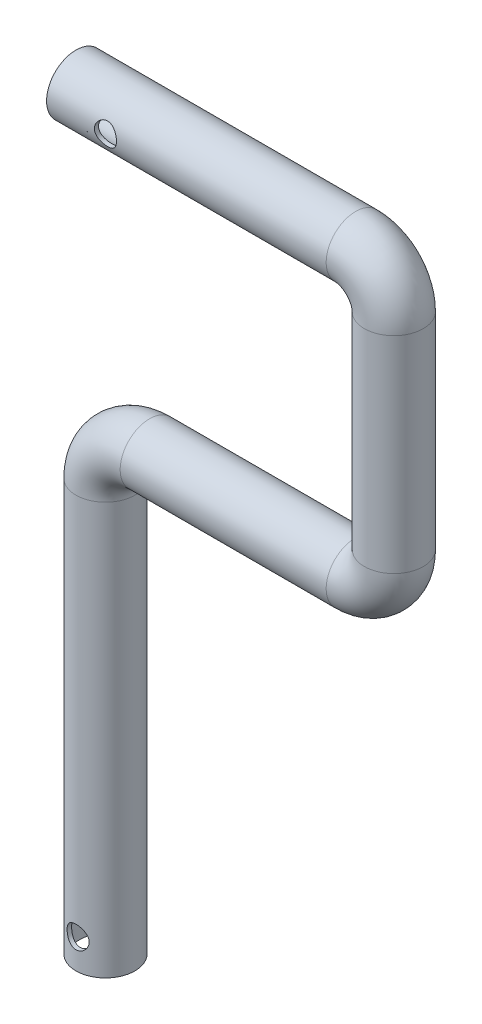
SolidWorks part; units mm, degrees
ref_plane "Front Plane" through (0, 0, 0) normal (0, 0, 1) x (1, 0, 0)
ref_plane "Top Plane" through (0, 0, 0) normal (0, 1, 0) x (1, 0, 0)
ref_plane "Right Plane" through (0, 0, 0) normal (1, 0, 0) x (0, 0, -1)
sketch "Sketch1" plane through (0, 0, 0) normal (0, 1, 0) x (1, 0, 0)
  circle A0 centre (0, 0) radius 5.461
  circle A1 centre (0, 0) radius 6.35
  dimension "D1" = 12.7
  dimension "D2" = 0.889
extrude "Boss-Extrude1" add sketch "Sketch1" along normal blind 88.9
sketch "Sketch5" plane through (0, 88.9, 0) normal (0, 1, 0) x (1, 0, 0)
  circle A0 centre (0, 0) radius 5.461
  circle A1 centre (0, 0) radius 6.35
  dimension "D1" = 12.7
  dimension "D2" = 0.889
sketch "Sketch6" plane through (0, 88.9, 0) normal (0, 1, 0) x (1, 0, 0)
  line L0 (9.525, 7.4909) -> (9.525, -7.4909) construction
  circle A0 centre (0, 0) radius 6.35 construction
  point P3 (6.35, 0)
  dimension "D1" = 9.525
revolve "Revolve2" add sketch "Sketch5" angle 90 about L0
sketch "Sketch7" plane through (9.525, 0, 0) normal (1, 0, 0) x (0, 0, -1)
  line L0 (0, 8.7313) -> (0, -8.7313) construction
  circle A0 centre (0, 98.425) radius 6.35
  circle A1 centre (0, 98.425) radius 6.35 construction
  circle A2 centre (0, 98.425) radius 5.461
  dimension "D1" = 0.889
extrude "Boss-Extrude2" add sketch "Sketch7" along normal blind 44.45
sketch "Sketch8" plane through (53.975, 0, 0) normal (1, 0, 0) x (0, 0, -1)
  line L0 (0, 33.1788) -> (0, -33.1788) construction
  circle A0 centre (0, 98.425) radius 6.35
  circle A1 centre (0, 98.425) radius 6.35 construction
  circle A2 centre (0, 98.425) radius 5.461
  dimension "D1" = 0.889
sketch "Sketch9" plane through (53.975, 0, 0) normal (1, 0, 0) x (0, 0, -1)
  line L0 (-10.2042, 106.68) -> (10.2042, 106.68) construction
  point P3 (0, 106.68)
  dimension "D1" = 8.255
revolve "Revolve3" add sketch "Sketch8" angle 90 about L0
sketch "Sketch10" plane through (0, 106.68, 0) normal (0, 1, 0) x (1, 0, 0)
  line L0 (-41.2115, 0) -> (41.2115, 0) construction
  line L1 (0, -11.2246) -> (0, 11.2246) construction
  circle A0 centre (62.23, 0) radius 6.35
  circle A1 centre (62.23, 0) radius 5.461
  circle A2 centre (62.23, 0) radius 6.35 construction
  point P5 (0, 0)
  point P6 (58.8154, 0)
  dimension "D1" = 12.7
  dimension "D2" = 0.889
  dimension "D3" = 62.23
extrude "Boss-Extrude3" add sketch "Sketch10" along normal blind 44.45
sketch "Sketch11" plane through (0, 151.13, 0) normal (0, 1, 0) x (1, 0, 0)
  circle A0 centre (62.23, 0) radius 5.461
  circle A1 centre (62.23, 0) radius 6.35
  point P4 (53.975, 0)
  dimension "D1" = 12.7
  dimension "D2" = 0.889
sketch "Sketch12" plane through (0, 151.13, 0) normal (0, 1, 0) x (1, 0, 0)
  line L0 (53.975, 10.2042) -> (53.975, -10.2042) construction
  line L2 (53.975, -10.2042) -> (53.975, 10.2042) construction
  circle A0 centre (62.23, 0) radius 6.35 construction
  point P4 (53.975, 0)
  dimension "D1" = 8.255
revolve "Revolve4" add sketch "Sketch11" angle 90 about L0
sketch "Sketch13" plane through (53.975, 0, 0) normal (-1, 0, 0) x (0, 0, 1)
  line L0 (0, -41.2115) -> (0, 41.2115) construction
  circle A0 centre (0, 159.385) radius 6.35
  circle A1 centre (0, 159.385) radius 6.35 construction
  circle A2 centre (0, 159.385) radius 5.461
  dimension "D1" = 0.889
extrude "Boss-Extrude4" add sketch "Sketch13" along normal blind 60.325
sketch "Sketch14" plane through (0, 0, 0) normal (0, 0, 1) x (1, 0, 0)
  line L0 (0, -6.985) -> (0, 6.985) construction
  line L1 (6.985, 0) -> (-6.985, 0) construction
  line L2 (-6.35, 165.735) -> (-6.35, 153.035) construction
  line L3 (-6.35, 153.035) -> (53.975, 153.035) construction
  circle A0 centre (6.35, 159.385) radius 2.3813
  circle A2 centre (0, 6.35) radius 2.3813
  dimension "D1" = 4.7625
  dimension "D4" = 4.7625
  dimension "D2" = 12.7
  dimension "D3" = 6.35
  dimension "D5" = 6.35
extrude "Cut-Extrude3" cut sketch "Sketch14" against normal mid plane 25.4
